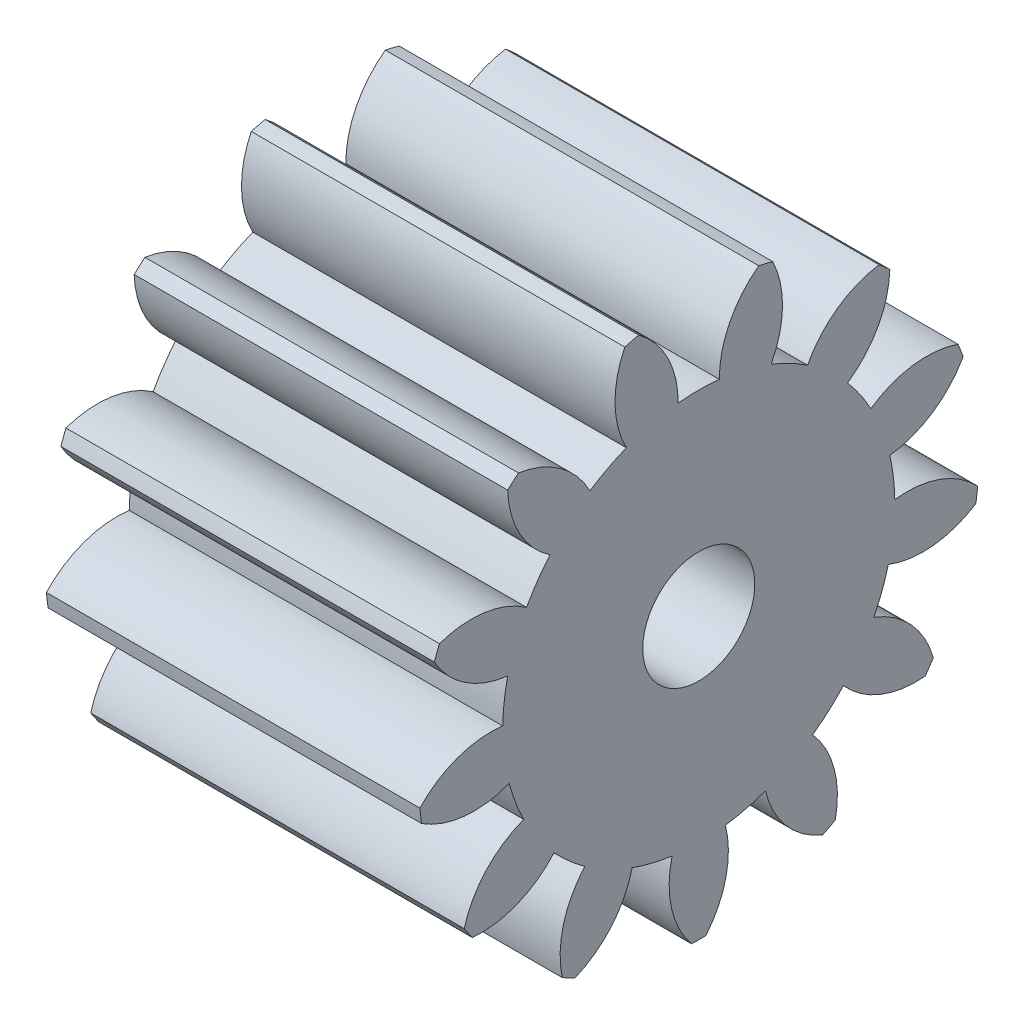
SolidWorks part; units mm, degrees
ref_plane "Front Plane" through (0, 0, 0) normal (0, 0, 1) x (1, 0, 0)
ref_plane "Top Plane" through (0, 0, 0) normal (0, 1, 0) x (1, 0, 0)
ref_plane "Right Plane" through (0, 0, 0) normal (1, 0, 0) x (0, 0, -1)
ref_plane "Plane1" through (8.2809, 0, 0) normal (1, 0, 0) x (0, 0, -1)
sketch "Sketch1" plane through (8.2809, 0, 0) normal (1, 0, 0) x (0, 0, -1)
  arc A0 (-5.2411, 5.47) -> (-4.1088, 3.4038) centre (-2.6424, 5.5507) ccw
  arc A1 (-4.1088, 3.4038) -> (-4.7343, 2.4977) centre (-0.1255, -0.0146) ccw
  arc A2 (-4.7343, 2.4977) -> (-7.0677, 2.8237) centre (-6.2217, 0.3652) ccw
  arc A3 (-7.0677, 2.8237) -> (-7.204, 2.4644) centre (-0.1255, -0.0146) ccw
  arc A4 (-7.204, 2.4644) -> (-5.2412, 1.1611) centre (-4.9404, 3.7436) ccw
  arc A5 (-5.2412, 1.1611) -> (-5.3739, 0.0681) centre (-0.1255, -0.0146) ccw
  arc A6 (-5.3739, 0.0681) -> (-7.5916, -0.7276) centre (-5.6999, -2.5114) ccw
  arc A7 (-7.5916, -0.7276) -> (-7.5452, -1.1091) centre (-0.1255, -0.0146) ccw
  arc A8 (-7.5452, -1.1091) -> (-5.2016, -1.351) centre (-6.1355, 1.0755) ccw
  arc A9 (-5.2016, -1.351) -> (-4.8111, -2.3804) centre (-0.1255, -0.0146) ccw
  arc A10 (-4.8111, -2.3804) -> (-6.405, -4.1156) centre (-3.9011, -4.8159) ccw
  arc A11 (-6.405, -4.1156) -> (-6.1867, -4.4318) centre (-0.1255, -0.0146) ccw
  arc A12 (-6.1867, -4.4318) -> (-3.9991, -3.5568) centre (-5.9537, -1.8423) ccw
  arc A13 (-3.9991, -3.5568) -> (-3.175, -4.2869) centre (-0.1255, -0.0146) ccw
  arc A14 (-3.175, -4.2869) -> (-3.7799, -6.5641) centre (-1.2374, -6.0206) ccw
  arc A15 (-3.7799, -6.5641) -> (-3.4397, -6.7426) centre (-0.1255, -0.0146) ccw
  arc A16 (-3.4397, -6.7426) -> (-1.9093, -4.9512) centre (-4.4367, -4.3414) ccw
  arc A17 (-1.9093, -4.9512) -> (-0.8403, -5.2147) centre (-0.1255, -0.0146) ccw
  arc A18 (-0.8403, -5.2147) -> (-0.3176, -7.5122) centre (1.6811, -5.8493) ccw
  arc A19 (-0.3176, -7.5122) -> (0.0666, -7.5122) centre (-0.1255, -0.0146) ccw
  arc A20 (0.0666, -7.5122) -> (0.5892, -5.2147) centre (-1.9321, -5.8493) ccw
  arc A21 (0.5892, -5.2147) -> (1.6582, -4.9512) centre (-0.1255, -0.0146) ccw
  arc A22 (1.6582, -4.9512) -> (3.1886, -6.7426) centre (4.1857, -4.3414) ccw
  arc A23 (3.1886, -6.7426) -> (3.5289, -6.5641) centre (-0.1255, -0.0146) ccw
  arc A24 (3.5289, -6.5641) -> (2.924, -4.2869) centre (0.9863, -6.0206) ccw
  arc A25 (2.924, -4.2869) -> (3.7481, -3.5568) centre (-0.1255, -0.0146) ccw
  arc A26 (3.7481, -3.5568) -> (5.9357, -4.4318) centre (5.7026, -1.8423) ccw
  arc A27 (5.9357, -4.4318) -> (6.154, -4.1156) centre (-0.1255, -0.0146) ccw
  arc A28 (6.154, -4.1156) -> (4.5601, -2.3804) centre (3.6501, -4.8159) ccw
  arc A29 (4.5601, -2.3804) -> (4.9505, -1.351) centre (-0.1255, -0.0146) ccw
  arc A30 (4.9505, -1.351) -> (7.2942, -1.1091) centre (5.8844, 1.0755) ccw
  arc A31 (7.2942, -1.1091) -> (7.3405, -0.7276) centre (-0.1255, -0.0146) ccw
  arc A32 (7.3405, -0.7276) -> (5.1228, 0.0681) centre (5.4489, -2.5114) ccw
  arc A33 (5.1228, 0.0681) -> (4.9901, 1.1611) centre (-0.1255, -0.0146) ccw
  arc A34 (4.9901, 1.1611) -> (6.9529, 2.4644) centre (4.6894, 3.7436) ccw
  arc A35 (6.9529, 2.4644) -> (6.8167, 2.8237) centre (-0.1255, -0.0146) ccw
  arc A36 (6.8167, 2.8237) -> (4.4832, 2.4977) centre (5.9707, 0.3652) ccw
  arc A37 (4.4832, 2.4977) -> (3.8578, 3.4038) centre (-0.1255, -0.0146) ccw
  arc A38 (3.8578, 3.4038) -> (4.9901, 5.47) centre (2.3913, 5.5507) ccw
  arc A39 (4.9901, 5.47) -> (4.7025, 5.7248) centre (-0.1255, -0.0146) ccw
  arc A40 (4.7025, 5.7248) -> (2.7878, 4.3517) centre (5.0959, 3.1547) ccw
  arc A41 (2.7878, 4.3517) -> (1.8129, 4.8633) centre (-0.1255, -0.0146) ccw
  arc A42 (1.8129, 4.8633) -> (1.8553, 7.2191) centre (-0.4833, 6.0829) ccw
  arc A43 (1.8553, 7.2191) -> (1.4822, 7.311) centre (-0.1255, -0.0146) ccw
  arc A44 (1.4822, 7.311) -> (0.425, 5.2054) centre (3.0249, 5.2182) ccw
  arc A45 (0.425, 5.2054) -> (-0.676, 5.2054) centre (-0.1255, -0.0146) ccw
  arc A46 (-0.676, 5.2054) -> (-1.7333, 7.311) centre (-3.276, 5.2182) ccw
  arc A47 (-1.7333, 7.311) -> (-2.1063, 7.2191) centre (-0.1255, -0.0146) ccw
  arc A48 (-2.1063, 7.2191) -> (-2.064, 4.8633) centre (0.2323, 6.0829) ccw
  arc A49 (-2.064, 4.8633) -> (-3.0388, 4.3517) centre (-0.1255, -0.0146) ccw
  arc A50 (-3.0388, 4.3517) -> (-4.9535, 5.7248) centre (-5.3469, 3.1547) ccw
  arc A51 (-4.9535, 5.7248) -> (-5.2411, 5.47) centre (-0.1255, -0.0146) ccw
  circle A52 centre (-0.1255, -0.0146) radius 1.5
extrude "Boss-Extrude1" add sketch "Sketch1" against normal blind 10
